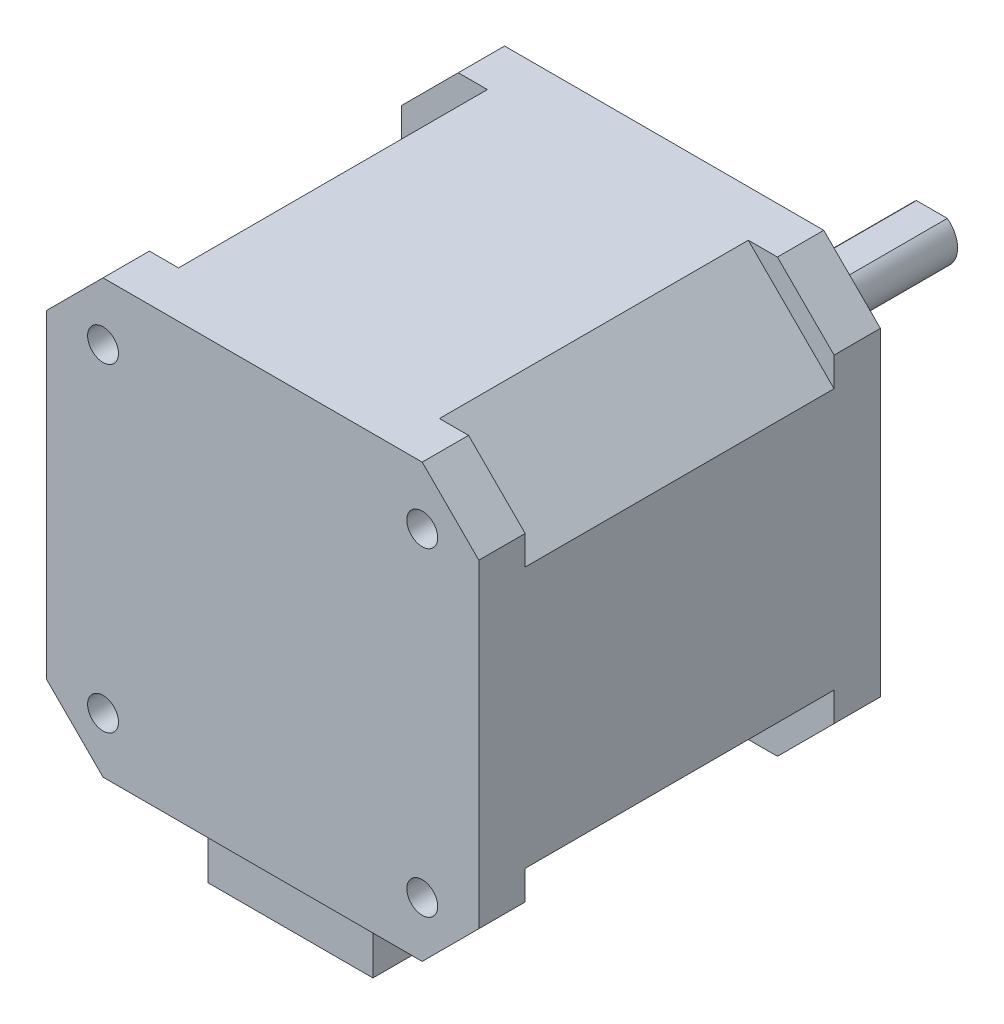
SolidWorks part; units mm, degrees
ref_plane "Front Plane" through (0, 0, 0) normal (0, 0, 1) x (1, 0, 0)
ref_plane "Top Plane" through (0, 0, 0) normal (0, 1, 0) x (1, 0, 0)
ref_plane "Right Plane" through (0, 0, 0) normal (1, 0, 0) x (0, 0, -1)
sketch "Sketch1" plane through (0, 0, 0) normal (0, 0, 1) x (1, 0, 0)
  line L0 (0, 36.5) -> (5.5, 42)
  line L1 (5.5, 0) -> (36.5, 0)
  line L2 (0, 5.5) -> (0, 36.5)
  line L3 (5.5, 42) -> (36.5, 42)
  line L4 (42, 5.5) -> (42, 36.5)
  line L5 (46.9904, 21) -> (-17.2499, 21) construction
  line L6 (21, 53.7645) -> (21, 0) construction
  line L7 (0, 5.5) -> (5.5, 0)
  line L8 (42, 5.5) -> (36.5, 0)
  line L9 (42, 36.5) -> (36.5, 42)
  circle A0 centre (5.5, 36.3827) radius 1.5
  circle A1 centre (36.5, 36.3827) radius 1.5
  circle A2 centre (36.5, 5.3827) radius 1.5
  circle A3 centre (5.5, 5.3827) radius 1.5
  point P2 (0, 42)
  point P7 (21, 42)
  dimension "D2" = 15.5
  dimension "D3" = 2
  dimension "3" = 3
  dimension "D4" = 2
extrude "Boss-Extrude1" add sketch "Sketch1" along normal blind 4.5
sketch "Sketch2" plane through (0, 0, 4.5) normal (0, 0, 1) x (1, 0, 0)
  line L0 (8.3284, 42) -> (0, 33.6716)
  line L1 (0, 8.3284) -> (8.3284, 0)
  line L2 (33.6716, 0) -> (42, 8.3284)
  line L3 (42, 33.6716) -> (33.6716, 42)
  line L4 (1.4142, 6.9142) -> (6.9142, 1.4142) construction
  line L5 (6.9142, 40.5858) -> (1.4142, 35.0858) construction
  line L6 (40.5858, 35.0858) -> (35.0858, 40.5858) construction
  line L7 (35.0858, 1.4142) -> (40.5858, 6.9142) construction
  line L8 (36.5, 42) -> (5.5, 42)
  line L9 (5.5, 42) -> (0, 36.5)
  line L10 (0, 36.5) -> (0, 5.5)
  line L11 (0, 5.5) -> (5.5, 0)
  line L12 (5.5, 0) -> (36.5, 0)
  line L13 (36.5, 0) -> (42, 5.5)
  line L14 (42, 5.5) -> (42, 36.5)
  line L15 (42, 36.5) -> (36.5, 42)
  line L16 (33.6716, 42) -> (8.3284, 42)
  line L17 (5.5, 42) -> (0, 36.5) construction
  line L18 (0, 33.6716) -> (0, 8.3284)
  line L19 (0, 5.5) -> (5.5, 0) construction
  line L20 (8.3284, 0) -> (33.6716, 0)
  line L21 (36.5, 0) -> (42, 5.5) construction
  line L22 (42, 8.3284) -> (42, 33.6716)
  line L23 (42, 36.5) -> (36.5, 42) construction
  dimension "D2" = 2
  dimension "D1" = 0
extrude "Boss-Extrude2" add sketch "Sketch2" along normal blind 30
sketch "Sketch3" plane through (0, 0, 34.5) normal (0, 0, 1) x (1, 0, 0)
  line L8 (36.5, 42) -> (5.5, 42)
  line L9 (42, 36.5) -> (36.5, 42)
  line L10 (42, 5.5) -> (42, 36.5)
  line L11 (36.5, 0) -> (42, 5.5)
  line L12 (5.5, 0) -> (36.5, 0)
  line L13 (0, 5.5) -> (5.5, 0)
  line L14 (0, 36.5) -> (0, 5.5)
  line L15 (5.5, 42) -> (0, 36.5)
  line L16 (36.5, 42) -> (5.5, 42)
  line L17 (42, 36.5) -> (36.5, 42)
  line L18 (42, 5.5) -> (42, 36.5)
  line L19 (36.5, 0) -> (42, 5.5)
  line L20 (5.5, 0) -> (36.5, 0)
  line L21 (0, 5.5) -> (5.5, 0)
  line L22 (0, 36.5) -> (0, 5.5)
  line L23 (5.5, 42) -> (0, 36.5)
  circle A0 centre (5.5, 5.3827) radius 1.5 construction
  circle A1 centre (36.5, 5.3827) radius 1.5 construction
  circle A2 centre (5.5, 36.3827) radius 1.5 construction
  circle A3 centre (36.5, 36.3827) radius 1.5 construction
  circle A4 centre (5.5, 5.3827) radius 1.5
  circle A5 centre (36.5, 5.3827) radius 1.5
  circle A6 centre (5.5, 36.3827) radius 1.5
  circle A7 centre (36.5, 36.3827) radius 1.5
  dimension "D1" = 0
extrude "Boss-Extrude3" add sketch "Sketch3" along normal blind 4.5
sketch "Sketch5" plane through (0, 0, 0) normal (0, 0, -1) x (-1, 0, 0)
  line L0 (-21, 42) -> (-21, 0) construction
  line L1 (-42, 21) -> (0, 21) construction
  line L8 (-5.5, 42) -> (-36.5, 42)
  line L9 (-36.5, 42) -> (-42, 36.5)
  line L10 (-42, 36.5) -> (-42, 5.5)
  line L11 (-42, 5.5) -> (-36.5, 0)
  line L12 (-36.5, 0) -> (-5.5, 0)
  line L13 (-5.5, 0) -> (0, 5.5)
  line L14 (0, 5.5) -> (0, 36.5)
  line L15 (0, 36.5) -> (-5.5, 42)
  line L16 (-5.5, 42) -> (-36.5, 42) construction
  line L17 (-36.5, 42) -> (-42, 36.5) construction
  line L18 (-42, 36.5) -> (-42, 5.5) construction
  line L19 (-42, 5.5) -> (-36.5, 0) construction
  line L20 (-36.5, 0) -> (-5.5, 0) construction
  line L21 (-5.5, 0) -> (0, 5.5) construction
  line L22 (0, 5.5) -> (0, 36.5) construction
  line L23 (0, 36.5) -> (-5.5, 42) construction
  circle A0 centre (-21, 21) radius 11
  point P14 (0, 0)
  dimension "D4" = 22
  dimension "D2" = 42
  dimension "D3" = 42
  dimension "D1" = 0
extrude "Boss-Extrude4" add sketch "Sketch5" along normal blind 2
sketch "Sketch6" plane through (0, 0, -2) normal (0, 0, -1) x (-1, 0, 0)
  circle A0 centre (-21, 21) radius 2.5
  circle A1 centre (-21, 21) radius 11
  circle A2 centre (-21, 21) radius 11 construction
  dimension "D1" = 0
extrude "Boss-Extrude5" add sketch "Sketch6" along normal blind 24
sketch "Sketch7" plane through (0, 0, 0) normal (-1, 0, 0) x (0, 0, 1)
  line L0 (-26, 23.5) -> (-26, 18.5) construction
  line L1 (-26, 23.5) -> (-26, 18.5) construction
  line L2 (-2, 23.5) -> (-2, 18.5) construction
  line L3 (-2, 23.5) -> (-2, 18.5) construction
  line L4 (-26, 23.5) -> (-12, 23.5)
  line L5 (-2, 23.5) -> (-26, 23.5) construction
  line L6 (-12, 23.5) -> (-12, 23)
  line L7 (-12, 23) -> (-26, 23)
  line L8 (-26, 23) -> (-26, 23.5)
  line L10 (-26, 18.5) -> (-2, 18.5) construction
  dimension "D1" = 14
  dimension "D2" = 4.5
  dimension "D3" = 14
extrude "Cut-Extrude2" cut sketch "Sketch7" against normal through all
sketch "Sketch8" plane through (0, 0, 0) normal (0, -1, 0) x (1, 0, 0)
  line L0 (21, 36.2858) -> (21, 0) construction
  line L3 (5.5, 39) -> (36.5, 39) construction
  line L4 (5.5, 0) -> (36.5, 0) construction
  line L5 (13, 36.2858) -> (21, 36.2858)
  line L6 (21, 39) -> (13, 39)
  line L8 (21, 28) -> (13, 28)
  line L9 (13, 36.2858) -> (13, 28)
  line L10 (21, 28) -> (29, 28)
  line L11 (21, 36.2858) -> (29, 36.2858)
  line L12 (29, 36.2858) -> (29, 28)
  dimension "D1" = 39
  dimension "D2" = 11
  dimension "D3" = 8
  dimension "D4" = 8
  dimension "D5" = 8
  dimension "D6" = 8
  dimension "D7" = 8.2858
extrude "Boss-Extrude6" add sketch "Sketch8" along normal blind 6.5 contours L0 L5 L9 L8 | L11 L0 L10 L12
